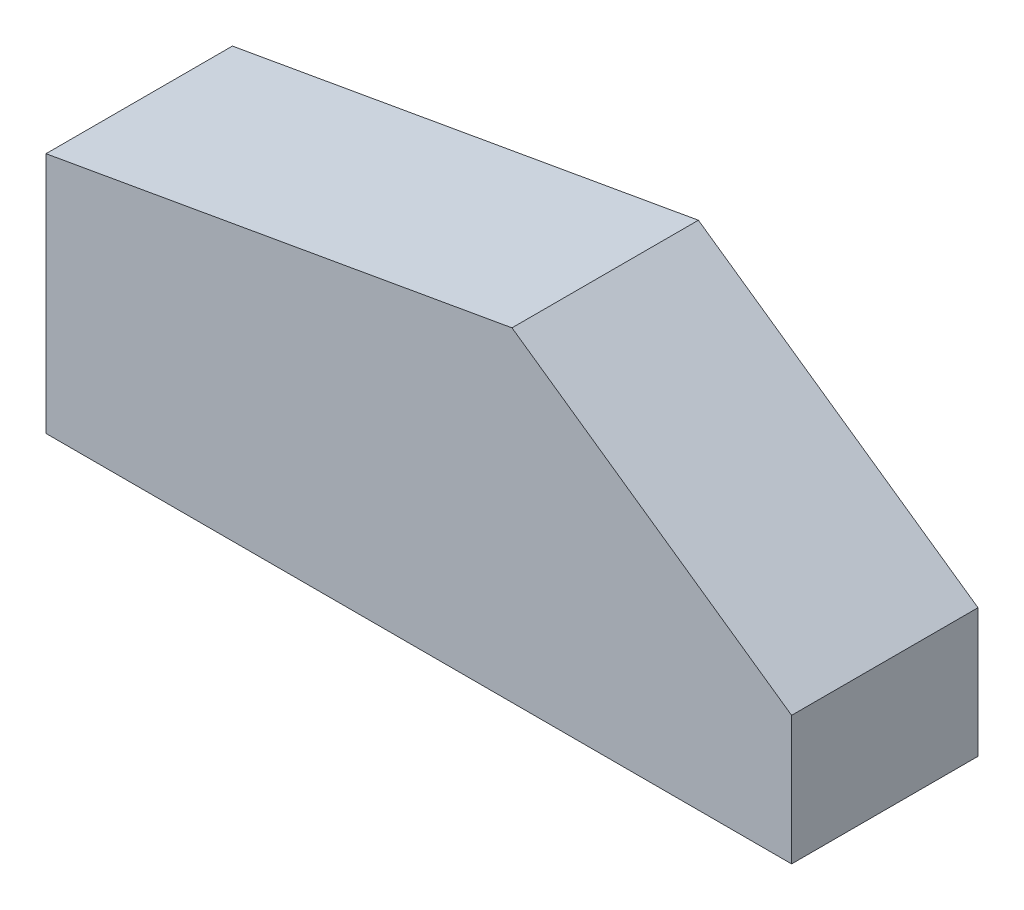
SolidWorks part; units mm, degrees
ref_plane "Alzado" through (0, 0, 0) normal (0, 0, 1) x (1, 0, 0)
ref_plane "Planta" through (0, 0, 0) normal (0, 1, 0) x (1, 0, 0)
ref_plane "Vista lateral" through (0, 0, 0) normal (1, 0, 0) x (0, 0, -1)
sketch "Croquis1" plane through (0, 0, 0) normal (0, 0, 1) x (1, 0, 0)
  line L0 (0, 0) -> (0, 13)
  line L1 (0, 0) -> (40, 0)
  line L2 (40, 0) -> (40, 6.9051)
  line L3 (0, 13) -> (25, 17.4082)
  line L4 (25, 17.4082) -> (40, 6.9051)
  dimension "D1" = 100
  dimension "D2" = 135
  dimension "D3" = 25
  dimension "D4" = 13
  dimension "D5" = 40
sketch "Croquis3" plane through (0, 0, 0) normal (0, 0, 1) x (1, 0, 0)
extrude "Saliente-Extruir1" add sketch "Croquis1" along normal blind 10
